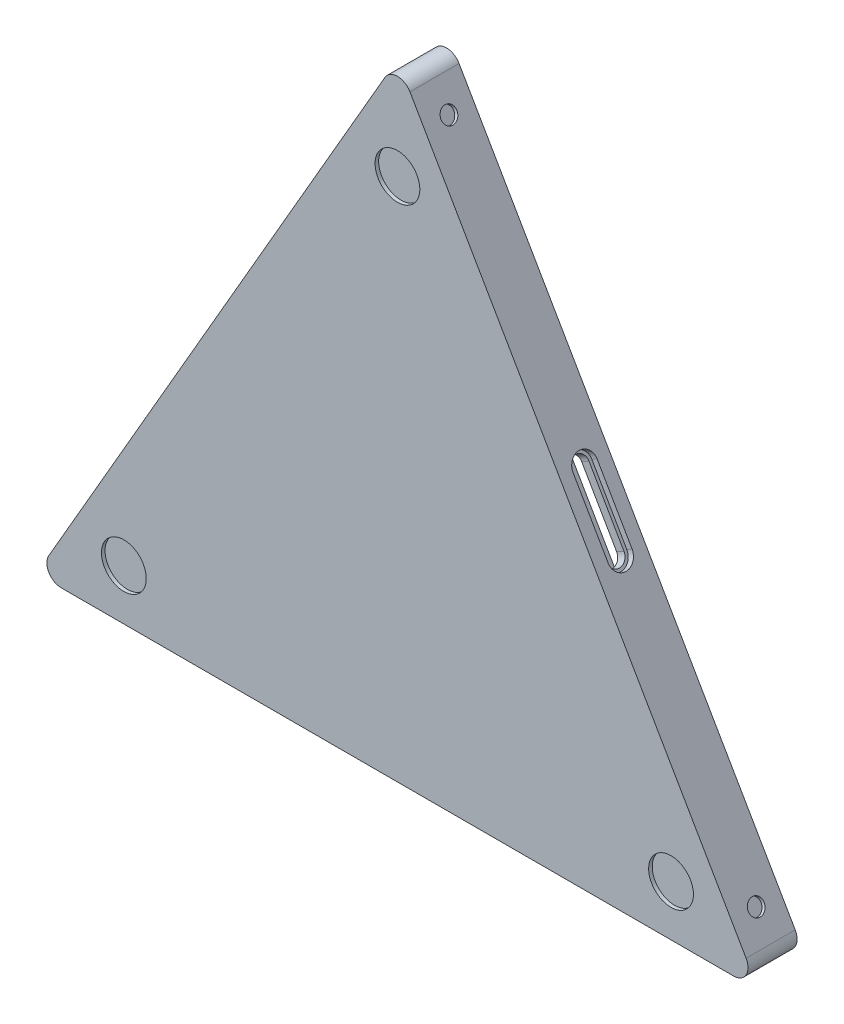
SolidWorks part; units mm, degrees
ref_plane "Plan de face" through (0, 0, 0) normal (0, 0, 1) x (1, 0, 0)
ref_plane "Plan de dessus" through (0, 0, 0) normal (0, 1, 0) x (1, 0, 0)
ref_plane "Plan de droite" through (0, 0, 0) normal (1, 0, 0) x (0, 0, -1)
sketch "Esquisse1" plane through (0, 0, 0) normal (0, 0, 1) x (1, 0, 0)
  line L0 (-188.4682, -62.2032) -> (-63.4682, 154.3031)
  line L1 (-63.4682, 154.3031) -> (61.5318, -62.2032)
  line L2 (61.5318, -62.2032) -> (-188.4682, -62.2032)
  line L3 (52.8715, -57.2032) -> (-179.808, -57.2032)
  line L4 (-179.808, -57.2032) -> (-63.4682, 144.3031)
  line L5 (-63.4682, 144.3031) -> (52.8715, -57.2032)
  dimension "D1" = 250
  dimension "D2" = 5
extrude "Boss.-Extru.1" add sketch "Esquisse1" along normal blind 15
sketch "Esquisse2" plane through (0, 0, 15) normal (0, 0, 1) x (1, 0, 0)
  line L0 (-63.4682, 154.3031) -> (-188.4682, -62.2032) construction
  line L1 (-188.4682, -62.2032) -> (61.5318, -62.2032) construction
  line L2 (61.5318, -62.2032) -> (-63.4682, 154.3031) construction
  line L3 (-63.4682, 154.3031) -> (-188.4682, -62.2032)
  line L4 (-188.4682, -62.2032) -> (61.5318, -62.2032)
  line L5 (61.5318, -62.2032) -> (-63.4682, 154.3031)
extrude "Boss.-Extru.2" add sketch "Esquisse2" along normal blind 2
sketch "Esquisse3" plane through (0, 0, 15) normal (0, 0, -1) x (-1, 0, 0)
  line L0 (55.5509, 120.5899) -> (-26.1807, -20.9734)
  line L1 (-52.8715, -57.2032) -> (63.4682, 144.3031) construction
  line L2 (55.5509, 120.5899) -> (56.8499, 119.8399)
  line L3 (56.8499, 119.8399) -> (-24.8817, -21.7234)
  line L4 (-24.8817, -21.7234) -> (-26.1807, -20.9734)
  line L5 (63.4682, 144.3031) -> (63.4682, -131.0717) construction
  line L6 (179.808, -57.2032) -> (-52.8715, -57.2032) construction
  line L7 (183.4817, -59.0358) -> (-91.5372, 99.7465) construction
  line L8 (-61.5318, -62.2032) -> (63.4682, 154.3031) construction
  line L21 (162.9805, -38.0572) -> (161.6815, -38.8072)
  line L22 (162.9805, -38.0572) -> (81.2489, 103.5061)
  line L23 (79.9499, 102.7561) -> (81.2489, 103.5061)
  line L24 (161.6815, -38.8072) -> (79.9499, 102.7561)
  line L25 (-52.8715, -57.2032) -> (184.8235, 80.03) construction
  line L26 (63.4682, 154.3031) -> (188.4682, -62.2032) construction
  line L31 (-27.627, -50.2704) -> (135.8362, -50.2704)
  line L32 (-27.627, -51.7704) -> (-27.627, -50.2704)
  line L33 (-27.627, -51.7704) -> (135.8362, -51.7704)
  line L34 (135.8362, -50.2704) -> (135.8362, -51.7704)
  dimension "D1" = 45
  dimension "D2" = 25
  dimension "D3" = 1.5
  dimension "D4" = 5
extrude "Boss.-Extru.3" add sketch "Esquisse3" along normal blind 11
sketch "Esquisse4" plane through (19.214, 11.0932, 0) normal (0.866, 0.5, 0) x (0, 0, -1)
  line L0 (0, 40.3645) -> (-17, 40.3645) construction
  line L1 (-12.65, 52.4645) -> (-4.35, 28.2645) construction
  line L3 (-12.65, 52.4645) -> (-12.65, 28.2645)
  line L5 (-4.35, 52.4645) -> (-4.35, 28.2645)
  line L6 (-4.35, 52.4645) -> (-12.65, 28.2645) construction
  arc A0 (-4.35, 52.4645) -> (-12.65, 52.4645) centre (-8.5, 52.4645) ccw
  arc A1 (-12.65, 28.2645) -> (-4.35, 28.2645) centre (-8.5, 28.2645) ccw
  point P4 (-8.5, 40.3645)
  point P6 (-8.5, 40.3645)
  point P8 (-8.5, 56.6145)
  point P11 (-8.5, 24.1145)
  dimension "D1" = 8.3
  dimension "D2" = 32.5
extrude "Enlèv. mat.-Extru.1" cut sketch "Esquisse4" against normal blind 2.1
sketch "Esquisse5" plane through (17.3954, 10.0432, 0) normal (0.866, 0.5, 0) x (0, 0, -1)
  line L4 (-11.65, 52.4645) -> (-11.65, 28.2645)
  line L5 (-5.35, 28.2645) -> (-5.35, 52.4645)
  line L6 (-11.65, 52.4645) -> (-11.65, 28.2645)
  line L7 (-5.35, 28.2645) -> (-5.35, 52.4645)
  arc A4 (-11.65, 28.2645) -> (-5.35, 28.2645) centre (-8.5, 28.2645) ccw
  arc A5 (-5.35, 52.4645) -> (-11.65, 52.4645) centre (-8.5, 52.4645) ccw
  arc A6 (-11.65, 28.2645) -> (-5.35, 28.2645) centre (-8.5, 28.2645) ccw
  arc A7 (-5.35, 52.4645) -> (-11.65, 52.4645) centre (-8.5, 52.4645) ccw
  dimension "D1" = 1
extrude "Enlèv. mat.-Extru.2" cut sketch "Esquisse5" against normal up to next
fillet "Congé1" radius 5 6 edges at (-179.808, -57.2032, 7.5) (52.8715, -57.2032, 7.5) (-63.4682, 144.3031, 7.5) (-63.4682, 154.3031, 8.5) (-188.4682, -62.2032, 8.5) (61.5318, -62.2032, 8.5)
ref_plane "Plan1" through (-11.5518, -20.0084, 0) normal (0.5, 0.866, 0) x (0.866, -0.5, 0)
mirror "Symétrie1" about plane through (-11.5518, -20.0084, 0) normal (0.5, 0.866, 0) of "Enlèv. mat.-Extru.2", "Enlèv. mat.-Extru.1"
sketch "Esquisse6" plane through (0, 0, 17) normal (0, 0, 1) x (1, 0, 0)
  line L0 (-63.4682, 149.3031) -> (-63.4682, -78.2575) construction
  line L1 (-4.4071, -24.1334) -> (-18.6966, -15.8834) construction
  arc A0 (-59.1381, 146.8031) -> (-67.7984, 146.8031) centre (-63.4682, 144.3031) ccw construction
  circle A1 centre (-63.4682, 119.3031) radius 7.75
  circle A2 centre (-158.1573, -44.7032) radius 7.75
  circle A3 centre (31.2209, -44.7032) radius 7.75
  dimension "D1" = 15.5
  dimension "D2" = 30
extrude "Enlèv. mat.-Extru.3" cut sketch "Esquisse6" against normal blind 1.24
sketch "Esquisse7" plane through (0, -62.2032, 0) normal (0, -1, 0) x (1, 0, 0)
  line L0 (-179.808, 8.5) -> (52.8715, 8.5) construction
  line L1 (-179.808, 17) -> (-179.808, 0) construction
  line L2 (52.8715, 0) -> (52.8715, 17) construction
  line L3 (-63.4682, 17) -> (-63.4682, 0) construction
  line L4 (-179.808, 17) -> (52.8715, 17) construction
  line L5 (-179.808, 0) -> (52.8715, 0) construction
  circle A0 centre (42.8715, 8.5) radius 2.75
  circle A1 centre (-169.808, 8.5) radius 2.75
  dimension "D1" = 5.5
  dimension "D2" = 10
  dimension "D3" = 10
extrude "Enlèv. mat.-Extru.4" cut sketch "Esquisse7" against normal blind 1.24
mirror "Symétrie2" about plane through (-11.5518, -20.0084, 0) normal (0.5, 0.866, 0) of "Enlèv. mat.-Extru.4"
ref_plane "Plan2" through (-20.1823, 34.9567, 0) normal (0.5, -0.866, 0) x (-0.866, -0.5, 0)
mirror "Symétrie3" about plane through (-20.1823, 34.9567, 0) normal (0.5, -0.866, 0) of "Enlèv. mat.-Extru.4"
sketch "Esquisse8" plane through (0, 0, 0) normal (0, 0, -1) x (-1, 0, 0)
  line L0 (18.6966, -15.8834) -> (4.4071, -24.1334) construction
  line L2 (-48.5414, -54.7032) -> (-57.2016, -59.7032) construction
  line L3 (13.0376, 39.0817) -> (27.327, 30.8317) construction
  circle A0 centre (-52.8715, -57.2032) radius 2.75
  arc A3 (-48.5414, -49.7032) -> (-44.2113, -57.2032) centre (-44.2113, -52.2032) ccw construction
  arc A4 (-57.2016, -54.7032) -> (-52.8715, -62.2032) centre (-52.8715, -57.2032) ccw construction
  circle A5 centre (63.4682, 144.3031) radius 2.75
  circle A6 centre (179.808, -57.2032) radius 2.75
  point P9 (0, 0)
  point P10 (-52.8715, -57.2032)
  point P16 (0, 0)
  dimension "D1" = 5.5
extrude "Enlèv. mat.-Extru.5" cut sketch "Esquisse8" against normal blind 2.48
